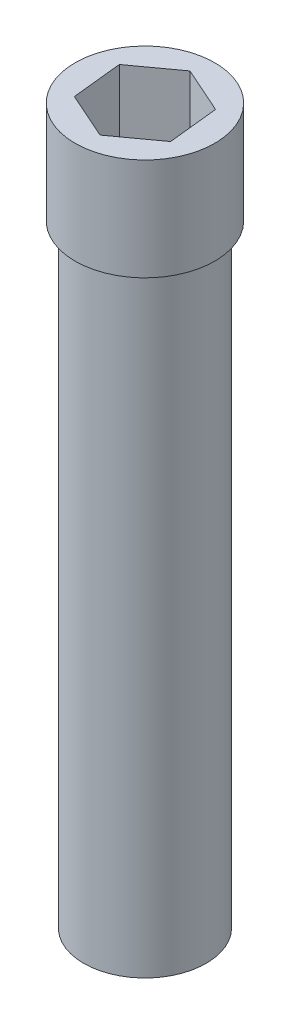
SolidWorks part; units mm, degrees
ref_plane "Front Plane" through (0, 0, 0) normal (0, 0, 1) x (1, 0, 0)
ref_plane "Top Plane" through (0, 0, 0) normal (0, 1, 0) x (1, 0, 0)
ref_plane "Right Plane" through (0, 0, 0) normal (1, 0, 0) x (0, 0, -1)
sketch "Sketch1" plane through (0, 0, 0) normal (0, 1, 0) x (1, 0, 0)
  circle A0 centre (0, 0) radius 3
  dimension "D1" = 6
extrude "Boss-Extrude1" add sketch "Sketch1" along normal blind 30
sketch "Sketch2" plane through (0, 30, 0) normal (0, 1, 0) x (1, 0, 0)
  circle A0 centre (0, 0) radius 3.4205
extrude "Boss-Extrude2" add sketch "Sketch2" along normal blind 5
sketch "Sketch3" plane through (0, 35, 0) normal (0, 1, 0) x (1, 0, 0)
  line L1 (-0.2588, 2.4623) -> (-2.2618, 1.007)
  line L2 (-2.2618, 1.007) -> (-2.003, -1.4552)
  line L3 (-2.003, -1.4552) -> (0.2588, -2.4623)
  line L4 (0.2588, -2.4623) -> (2.2618, -1.007)
  line L5 (2.2618, -1.007) -> (2.003, 1.4552)
  line L6 (2.003, 1.4552) -> (-0.2588, 2.4623)
  circle A0 centre (0, 0) radius 2.1441 construction
extrude "Cut-Extrude1" cut sketch "Sketch3" against normal blind 4
sketch "Sketch4" plane through (0, 0, 0) normal (0, -1, 0) x (-1, 0, 0)
  circle A0 centre (0, 0) radius 3
  dimension "D1" = 6
